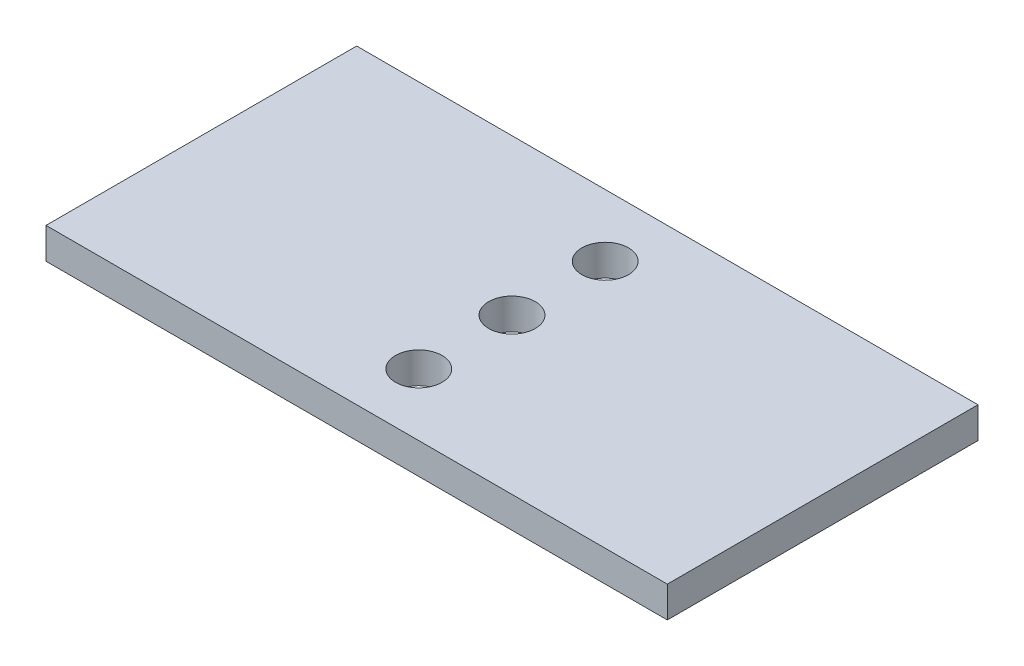
SolidWorks part; units mm, degrees
material "1060 Alloy"
ref_plane "Front Plane" through (0, 0, 0) normal (0, 0, 1) x (1, 0, 0)
ref_plane "Top Plane" through (0, 0, 0) normal (0, 1, 0) x (1, 0, 0)
ref_plane "Right Plane" through (0, 0, 0) normal (1, 0, 0) x (0, 0, -1)
sketch "Sketch2" plane through (0, 0, 0) normal (0, 1, 0) x (1, 0, 0)
  line L1 (100, -50) -> (-100, -50)
  line L2 (100, -50) -> (100, 50)
  line L3 (100, 50) -> (-100, 50)
  line L4 (-100, -50) -> (-100, 50)
  line L5 (100, -50) -> (-100, 50) construction
  line L6 (100, 50) -> (-100, -50) construction
  circle A0 centre (0, 0) radius 7.5
  circle A1 centre (0, 30) radius 7.5
  circle A2 centre (0, -30) radius 7.5
  point P0 (0, 0)
  dimension "D3" = 15
  dimension "D4" = 15
  dimension "D5" = 15
  dimension "D1" = 200
  dimension "D2" = 100
  dimension "D6" = 30
  dimension "D7" = 30
extrude "Boss-Extrude1" add sketch "Sketch2" along normal blind 10
